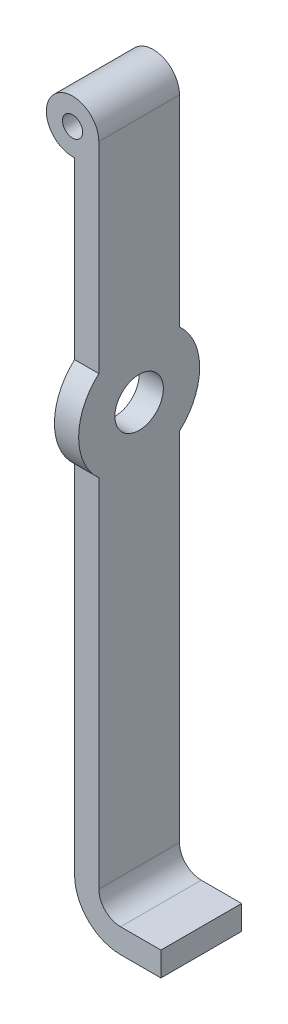
SolidWorks part; units mm, degrees
ref_plane "Front Plane" through (0, 0, 0) normal (0, 0, 1) x (1, 0, 0)
ref_plane "Top Plane" through (0, 0, 0) normal (0, 1, 0) x (1, 0, 0)
ref_plane "Right Plane" through (0, 0, 0) normal (1, 0, 0) x (0, 0, -1)
sketch "Sketch1" plane through (0, 0, 0) normal (0, 0, 1) x (1, 0, 0)
  line L0 (0.25, -3.2404) -> (0.25, -80.2404)
  line L2 (3.25, -80.2404) -> (3.25, 0)
  line L3 (5.95, -82.9404) -> (10.95, -82.9404)
  line L4 (10.95, -82.9404) -> (10.95, -85.9404)
  line L5 (10.95, -85.9404) -> (5.95, -85.9404)
  circle A0 centre (0, 0) radius 1.25
  arc A1 (3.25, 0) -> (0.25, -3.2404) centre (0, 0) ccw
  arc A2 (0.25, -80.2404) -> (5.95, -85.9404) centre (5.95, -80.2404) ccw
  arc A3 (3.25, -80.2404) -> (5.95, -82.9404) centre (5.95, -80.2404) ccw
  dimension "D1" = 2.5
  dimension "D2" = 2
  dimension "D5" = 5.4
  dimension "D7" = 3
  dimension "D3" = 3
  dimension "D4" = 77
  dimension "D6" = 5
extrude "Boss-Extrude1" add sketch "Sketch1" along normal blind 10
sketch "Sketch2" plane through (0.25, 0, 0) normal (-1, 0, 0) x (0, 0, 1)
  line L0 (10, -80.2404) -> (0, -80.2404) construction
  line L1 (5, -80.2404) -> (5, -3.2404) construction
  line L2 (10, -3.2404) -> (0, -3.2404) construction
  line L4 (5, 0) -> (17.3739, 0) construction
  circle A0 centre (5, -30.5) radius 3
  dimension "D2" = 6
  dimension "D1" = 30.5
extrude "Cut-Extrude1" cut sketch "Sketch2" against normal up to next
sketch "Sketch3" plane through (0.25, 0, 0) normal (-1, 0, 0) x (0, 0, 1)
  circle A0 centre (5, -30.5) radius 7.5
  circle A1 centre (5, -30.5) radius 3
  circle A2 centre (5, -30.5) radius 3 construction
  dimension "D1" = 15
extrude "Boss-Extrude2" add sketch "Sketch3" against normal up to surface (3 mm away) up to face at (3.25, -33.5, 5)
